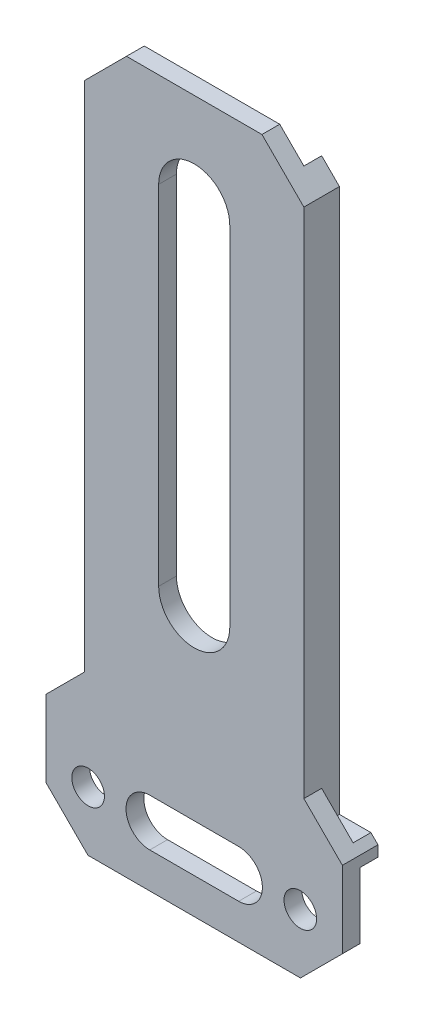
SolidWorks part; units mm, degrees
ref_plane "Front Plane" through (0, 0, 0) normal (0, 0, 1) x (1, 0, 0)
ref_plane "Top Plane" through (0, 0, 0) normal (0, 1, 0) x (1, 0, 0)
ref_plane "Right Plane" through (0, 0, 0) normal (1, 0, 0) x (0, 0, -1)
sketch "Sketch1" plane through (0, 0, 0) normal (0, 0, 1) x (1, 0, 0)
  line L0 (25, 120) -> (25, 0) construction
  line L1 (7.0711, 0) -> (42.9289, 0)
  line L2 (0, 7.0711) -> (0, 20)
  line L3 (13.5711, 120) -> (36.4289, 120)
  line L4 (50, 7.0711) -> (50, 20)
  line L5 (25, 45.27) -> (25, 104) construction
  line L6 (19, 45.27) -> (19, 104)
  line L7 (31, 45.27) -> (31, 104)
  line L8 (0, 10) -> (50, 10) construction
  line L9 (17.5, 10) -> (32.5, 10) construction
  line L10 (17.5, 14) -> (32.5, 14)
  line L11 (17.5, 6) -> (32.5, 6)
  line L12 (6.5, 112.9289) -> (6.5, 26.5)
  line L13 (6.5, 26.5) -> (0, 20)
  line L14 (43.5, 26.5) -> (50, 20)
  line L15 (43.5, 112.9289) -> (43.5, 26.5)
  line L16 (13.5711, 120) -> (6.5, 112.9289)
  line L17 (36.4289, 120) -> (43.5, 112.9289)
  line L18 (0, 7.0711) -> (7.0711, 0)
  line L19 (50, 7.0711) -> (42.9289, 0)
  line L20 (0, 7.0711) -> (0, 0) construction
  line L22 (0, 0) -> (7.0711, 0) construction
  arc A0 (19, 45.27) -> (31, 45.27) centre (25, 45.27) ccw
  arc A1 (31, 104) -> (19, 104) centre (25, 104) ccw
  circle A2 centre (7.1, 10) radius 2.75
  circle A3 centre (42.9, 10) radius 2.75
  arc A4 (17.5, 14) -> (17.5, 6) centre (17.5, 10) ccw
  arc A5 (32.5, 6) -> (32.5, 14) centre (32.5, 10) ccw
  point P9 (25, 74.635)
  point P22 (25, 10)
  dimension "D6" = 5.5
  dimension "D10" = 26.52
  dimension "D3" = 10
  dimension "D1" = 50
  dimension "D2" = 120
  dimension "D4" = 12
  dimension "D5" = 35.8
  dimension "D7" = 10
  dimension "D8" = 8
  dimension "D9" = 15
  dimension "D11" = 135
  dimension "D12" = 20
  dimension "D13" = 37
  dimension "D14" = 135
  dimension "D15" = 10
  dimension "D16" = 135
  dimension "D17" = 10
extrude "Boss-Extrude1" add sketch "Sketch1" along normal blind 3
sketch "Sketch2" plane through (0, 0, 0) normal (0, 0, -1) x (-1, 0, 0)
  line L0 (-50, 18.19) -> (0, 18.19)
  line L1 (-50, 7.0711) -> (-50, 20) construction
  line L2 (0, 20) -> (0, 7.0711) construction
  line L3 (-48.81, 21.19) -> (-43.5, 21.19)
  line L4 (-50, 20) -> (-43.5, 26.5) construction
  line L5 (-6.5, 26.5) -> (0, 20) construction
  line L6 (-48.81, 21.19) -> (-50, 20)
  line L7 (-50, 20) -> (-50, 18.19)
  line L8 (-1.19, 21.19) -> (0, 20)
  line L9 (0, 20) -> (0, 18.19)
  line L10 (-7.0711, 0) -> (-42.9289, 0) construction
  line L11 (-6.5, 112.9289) -> (-6.5, 21.19)
  line L12 (-9.5, 115.9289) -> (-9.5, 21.19)
  line L13 (-13.5711, 120) -> (-6.5, 112.9289) construction
  line L14 (-6.5, 112.9289) -> (-9.5, 115.9289)
  line L15 (-6.5, 21.19) -> (-1.19, 21.19)
  line L16 (-43.5, 112.9289) -> (-43.5, 21.19)
  line L17 (-40.5, 115.9289) -> (-40.5, 21.19)
  line L18 (-43.5, 112.9289) -> (-36.4289, 120) construction
  line L19 (-40.5, 115.9289) -> (-43.5, 112.9289)
  line L20 (-40.5, 21.19) -> (-9.5, 21.19)
  dimension "D1" = 3
  dimension "D2" = 18.19
  dimension "D3" = 3
  dimension "D4" = 3
extrude "Boss-Extrude2" add sketch "Sketch2" along normal blind 3
